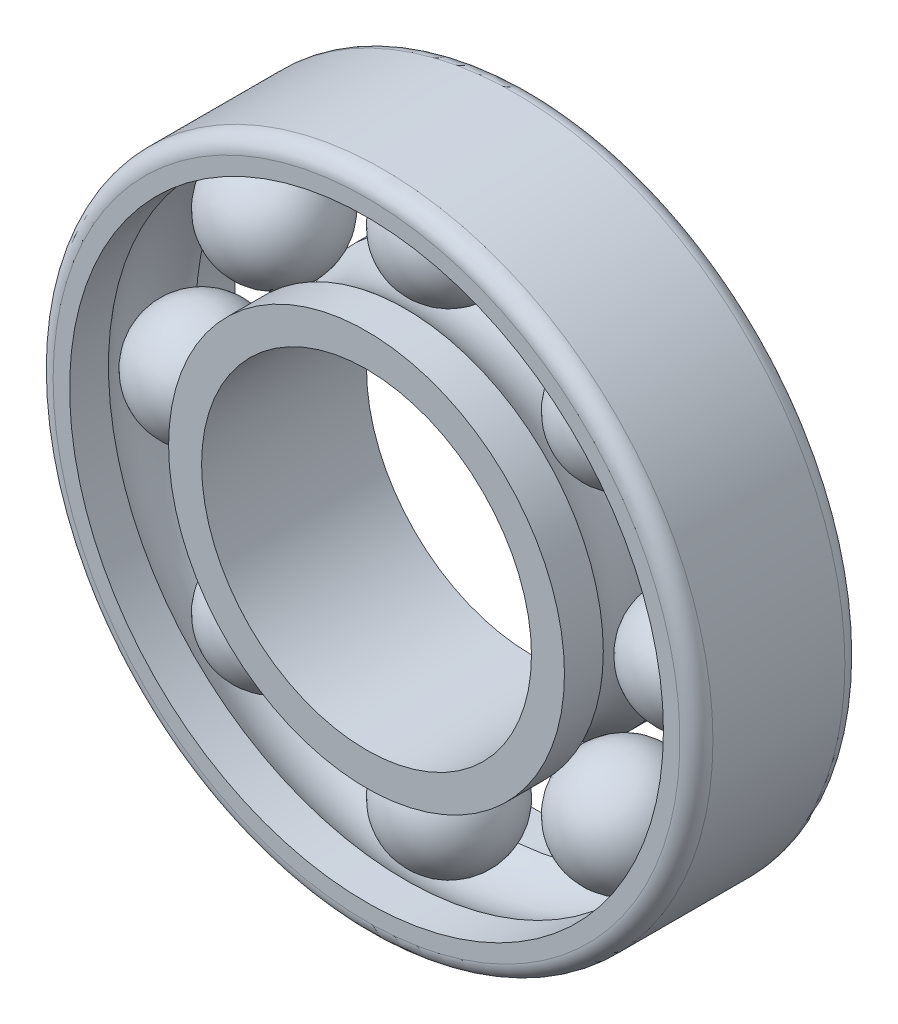
SolidWorks part; units mm, degrees
ref_plane "Front Plane" through (0, 0, 0) normal (0, 0, 1) x (1, 0, 0)
ref_plane "Top Plane" through (0, 0, 0) normal (0, 1, 0) x (1, 0, 0)
ref_plane "Right Plane" through (0, 0, 0) normal (1, 0, 0) x (0, 0, -1)
sketch "Sketch2" plane through (0, 0, 0) normal (0, 1, 0) x (1, 0, 0)
  line L0 (-1, 0.5) -> (-1.2, 0.3) construction
  line L1 (-1, 0.5) -> (-1.2, 0.5)
  line L2 (-1, 0.5) -> (-1, -0.5)
  line L3 (-1, -0.5) -> (-1.2, -0.5)
  line L4 (-1.2, 0.5) -> (-1.2, 0.2646)
  line L5 (-1, 0.5) -> (-1.2, -0.5) construction
  line L6 (-1, -0.5) -> (-1.2, 0.5) construction
  line L7 (-1.8, 0.5) -> (-2, 0.5)
  line L8 (-1.8, 0.5) -> (-1.8, 0.2646)
  line L9 (-1.8, -0.5) -> (-2, -0.5)
  line L10 (-2, 0.5) -> (-2, -0.5)
  line L11 (-1.8, 0.5) -> (-2, -0.5) construction
  line L12 (-1.8, -0.5) -> (-2, 0.5) construction
  line L13 (0, 0) -> (0, 1.1168) construction
  line L14 (-1.2, -0.2646) -> (-1.2, -0.5)
  line L15 (-1.8, -0.3) -> (-2, -0.5) construction
  line L16 (-1.8, -0.2646) -> (-1.8, -0.5)
  arc A0 (-1.8, 0.2646) -> (-1.8, -0.2646) centre (-1.5, 0) ccw
  arc A1 (-1.2, -0.2646) -> (-1.2, 0.2646) centre (-1.5, 0) ccw
  point P0 (-1.1, 0)
  point P5 (-1.9, 0)
  dimension "D1" = 1
  dimension "D2" = 0.2
  dimension "D3" = 2
  dimension "D4" = 1
sketch "Sketch3" plane through (0, 0, 0) normal (0, 1, 0) x (1, 0, 0)
  line L0 (-1.5, 0.3546) -> (-1.5, -0.3546)
  arc A0 (-1.5, 0.3546) -> (-1.5, -0.3546) centre (-1.5, 0) cw
revolve "Revolve1" add sketch "Sketch3" angle 360 about L0
revolve "Revolve2" add sketch "Sketch2" angle 360 about L13
pattern_circular "CirPattern1" count 8 over 360 about axis through (0, 0, 0) along (0, 0, 1) of bodies 101
fillet "Fillet1" radius 0.1 1 edges at (2, 0, -0.5)
fillet "Fillet2" radius 0.1 1 edges at (2, 0, 0.5)
